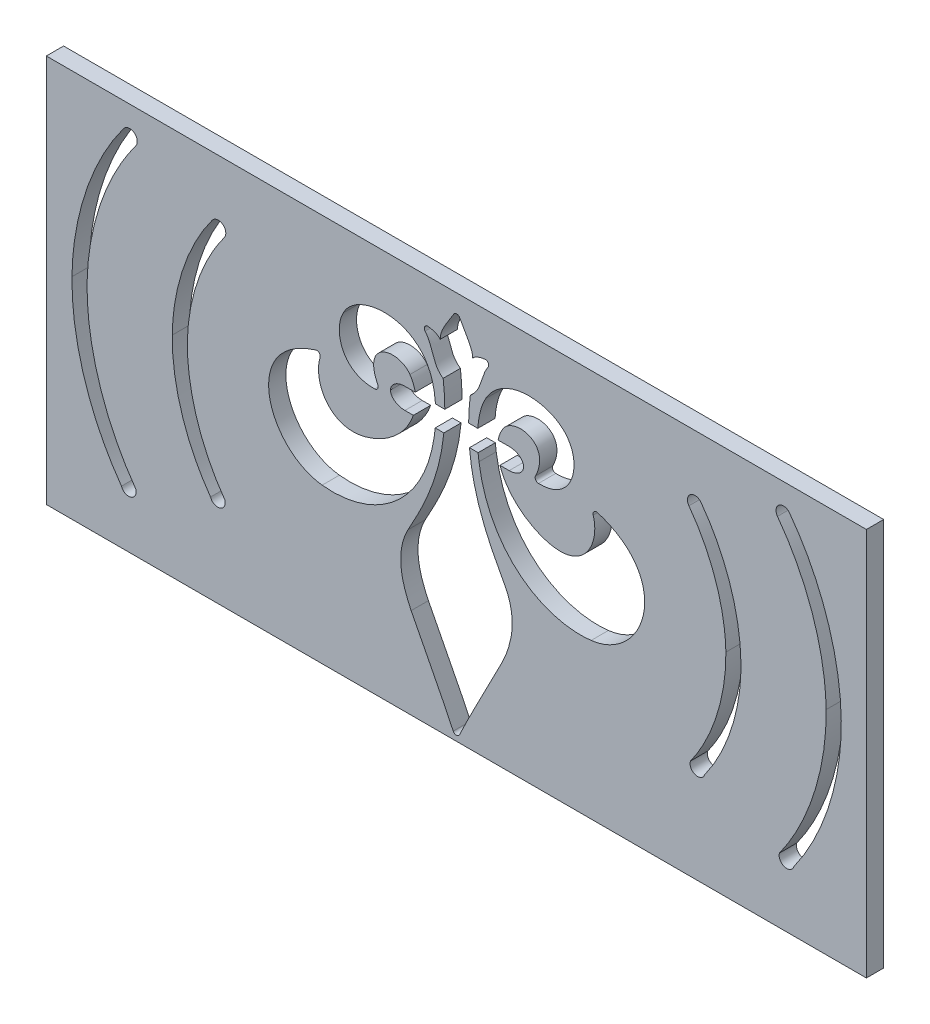
SolidWorks part; units mm, degrees
ref_plane "Front Plane" through (0, 0, 0) normal (0, 0, 1) x (1, 0, 0)
ref_plane "Top Plane" through (0, 0, 0) normal (0, 1, 0) x (1, 0, 0)
ref_plane "Right Plane" through (0, 0, 0) normal (1, 0, 0) x (0, 0, -1)
sketch "Model" plane through (0, 0, 0) normal (0, 0, 1) x (1, 0, 0)
  line L0 (-86.1627, 254.4051) -> (-87.51, 254.4051)
  line L1 (-81.5488, 254.4051) -> (-83.1766, 254.4051)
  line L2 (-82.907, 251.3309) -> (-81.5488, 251.3309)
  line L3 (-87.3892, 251.3309) -> (-86.1192, 251.3309)
  line L4 (-92.4284, 251.3309) -> (-91.1584, 251.3309)
  line L5 (-96.8828, 251.3309) -> (-95.641, 251.3309)
  line L6 (-95.3712, 254.4051) -> (-96.8828, 254.4051)
  line L7 (-91.0142, 254.4051) -> (-92.3852, 254.4051)
  line L9 (-149.6399, 270.1136) -> (-28.9899, 270.1136)
  line L10 (-149.6399, 270.1136) -> (-149.6399, 212.9636)
  line L11 (-149.6399, 212.9636) -> (-28.9899, 212.9636)
  line L12 (-28.9899, 270.1136) -> (-28.9899, 212.9636)
  arc A0 (-125.4824, 226.0089) -> (-123.3695, 226.6771) centre (-124.426, 226.343) ccw
  arc A1 (-123.4553, 260.0716) -> (-125.234, 261.3934) centre (-124.3446, 260.7325) ccw
  arc A2 (-138.5846, 220.8425) -> (-136.4718, 221.5108) centre (-137.5282, 221.1766) ccw
  arc A3 (-136.4853, 265.238) -> (-138.264, 266.5598) centre (-137.3746, 265.8989) ccw
  arc A4 (-101.3097, 251.8565) -> (-100.8693, 252.589) centre (-101.3249, 252.3643) ccw
  arc A5 (-93.4457, 263.7399) -> (-93.9132, 262.9175) centre (-93.5183, 263.2371) ccw
  arc A6 (-88.8174, 267.1636) -> (-89.7055, 267.1819) centre (-89.2665, 266.9262) ccw
  arc A7 (-84.6578, 262.9354) -> (-85.1365, 263.7421) centre (-85.065, 263.2391) ccw
  arc A8 (-77.6787, 252.589) -> (-77.2382, 251.8565) centre (-77.2231, 252.3643) ccw
  arc A9 (-68.5487, 252.4802) -> (-69.1861, 251.8483) centre (-68.6998, 251.9952) ccw
  arc A10 (-89.7766, 214.0218) -> (-88.8534, 214.0212) centre (-89.3149, 214.2336) ccw
  arc A11 (-109.3619, 251.8483) -> (-109.9993, 252.4802) centre (-109.8481, 251.9952) ccw
  arc A12 (-41.7763, 222.4942) -> (-39.6635, 221.826) centre (-40.7199, 222.1601) ccw
  arc A13 (-40.2952, 266.5598) -> (-42.0738, 265.238) centre (-41.1845, 265.8989) ccw
  arc A14 (-53.3252, 261.3934) -> (-55.1038, 260.0716) centre (-54.2145, 260.7325) ccw
  arc A15 (-54.8787, 227.6601) -> (-52.7658, 226.9919) centre (-53.8223, 227.326) ccw
  spline S0 degree 3 poles (-131.1142, 243.816) (-131.1919, 237.591) (-129.1255, 231.0571) (-125.4824, 226.0089) knots 0 0 0 0 1 1 1 1
  spline S1 degree 3 poles (-125.234, 261.3934) (-128.9192, 256.4345) (-131.0371, 249.9938) (-131.1142, 243.816) knots 0 0 0 0 1.00991 1.00991 1.00991 1.00991
  spline S2 degree 3 poles (-128.8933, 244.1428) (-128.7863, 249.7523) (-126.8018, 255.5685) (-123.4553, 260.0716) knots 0 0 0 0 0.989781 0.989781 0.989781 0.989781
  spline S3 degree 3 poles (-123.3695, 226.6771) (-126.9428, 231.6285) (-128.9696, 238.0371) (-128.8933, 244.1428) knots 0 0 0 0 1 1 1 1
  spline S4 degree 3 poles (-145.8693, 243.8758) (-145.9699, 235.8238) (-143.2969, 227.3724) (-138.5846, 220.8425) knots 0 0 0 0 1 1 1 1
  spline S5 degree 3 poles (-138.264, 266.5598) (-143.0208, 260.1588) (-145.7697, 251.8502) (-145.8693, 243.8758) knots 0 0 0 0 1.007595 1.007595 1.007595 1.007595
  spline S6 degree 3 poles (-143.6486, 244.203) (-143.5189, 251.609) (-140.9034, 259.2928) (-136.4853, 265.238) knots 0 0 0 0 0.992225 0.992225 0.992225 0.992225
  spline S7 degree 3 poles (-136.4718, 221.5108) (-141.1143, 227.9439) (-143.7476, 236.2703) (-143.6486, 244.203) knots 0 0 0 0 1 1 1 1
  spline S8 degree 3 poles (-84.9995, 258.7993) (-85.6984, 257.5657) (-86.0494, 256.0206) (-86.1627, 254.4051) knots 0 0 0 0 1 1 1 1
  spline S9 degree 3 poles (-77.2382, 251.8565) (-72.3494, 251.7108) (-71.0944, 256.5725) (-72.6186, 259.2579) knots 0.050131 0.050131 0.050131 0.050131 1 1 1 1
  spline S10 degree 3 poles (-82.4017, 256.2777) (-80.7172, 258.6942) (-75.2407, 257.5318) (-77.6787, 252.589) knots 0 0 0 0 0.958312 0.958312 0.958312 0.958312
  spline S11 degree 3 poles (-83.1766, 254.4051) (-83.053, 255.0746) (-82.7985, 255.7083) (-82.4017, 256.2777) knots 0 0 0 0 1 1 1 1
  spline S12 degree 3 poles (-79.4277, 252.868) (-79.4277, 253.7169) (-80.3774, 254.4051) (-81.5488, 254.4051) knots 0 0 0 0 1 1 1 1
  spline S13 degree 3 poles (-81.5488, 251.3309) (-80.3774, 251.3309) (-79.4277, 252.0189) (-79.4277, 252.868) knots 0 0 0 0 1 1 1 1
  spline S14 degree 3 poles (-69.1861, 251.8483) (-68.0118, 247.9626) (-71.2721, 242.3607) (-78.1228, 245.9626) knots 0.075744 0.075744 0.075744 0.075744 1 1 1 1
  spline S15 degree 3 poles (-69.4879, 235.7237) (-61.5111, 236.6377) (-57.1273, 248.9205) (-68.5487, 252.4802) knots 0 0 0 0 0.972274 0.972274 0.972274 0.972274
  spline S16 degree 3 poles (-85.9922, 250.2414) (-84.5404, 240.0027) (-76.8232, 234.8831) (-69.4879, 235.7237) knots 0 0 0 0 1 1 1 1
  spline S17 degree 3 poles (-86.1192, 251.3309) (-86.0854, 250.9628) (-86.0429, 250.5983) (-85.9922, 250.2414) knots 0 0 0 0 1 1 1 1
  spline S18 degree 3 poles (-82.1688, 236.3628) (-83.8899, 239.5677) (-86.7646, 244.3865) (-87.3892, 251.3309) knots 0 0 0 0 1 1 1 1
  spline S19 degree 3 poles (-82.6302, 226.285) (-81.7486, 228.1162) (-79.9377, 232.2086) (-82.1688, 236.3628) knots 0 0 0 0 1 1 1 1
  spline S20 degree 3 poles (-88.8534, 214.0212) (-87.2569, 217.4908) (-83.5264, 224.424) (-82.6302, 226.285) knots 0.104035 0.104035 0.104035 0.104035 1 1 1 1
  spline S21 degree 3 poles (-95.9666, 226.285) (-95.0705, 224.4242) (-91.3675, 217.4917) (-89.7766, 214.0218) knots 0 0 0 0 0.895912 0.895912 0.895912 0.895912
  spline S22 degree 3 poles (-96.4282, 236.3628) (-98.6593, 232.2086) (-96.8485, 228.1162) (-95.9666, 226.285) knots 0 0 0 0 1 1 1 1
  spline S23 degree 3 poles (-91.1584, 251.3309) (-91.8291, 244.4179) (-94.7187, 239.5458) (-96.4282, 236.3628) knots 0 0 0 0 1 1 1 1
  spline S24 degree 3 poles (-92.5553, 250.2414) (-92.5047, 250.5983) (-92.4618, 250.9626) (-92.4284, 251.3309) knots 0 0 0 0 1 1 1 1
  spline S25 degree 3 poles (-109.0598, 235.7237) (-101.7245, 234.8831) (-94.0073, 240.0025) (-92.5553, 250.2414) knots 0 0 0 0 1 1 1 1
  spline S26 degree 3 poles (-109.9993, 252.4802) (-121.4202, 248.9203) (-117.0365, 236.6376) (-109.0598, 235.7237) knots 0.027728 0.027728 0.027728 0.027728 1 1 1 1
  spline S27 degree 3 poles (-100.4252, 245.9626) (-107.2759, 242.3607) (-110.5361, 247.9625) (-109.3619, 251.8483) knots 0 0 0 0 0.924254 0.924254 0.924254 0.924254
  spline S28 degree 3 poles (-95.641, 251.3309) (-96.3355, 249.2549) (-98.0146, 247.2301) (-100.4252, 245.9626) knots 0 0 0 0 1 1 1 1
  spline S29 degree 3 poles (-99.0038, 252.868) (-99.0038, 252.019) (-98.0542, 251.3309) (-96.8828, 251.3309) knots 0 0 0 0 1 1 1 1
  spline S30 degree 3 poles (-96.8828, 254.4051) (-98.0542, 254.4051) (-99.0038, 253.717) (-99.0038, 252.868) knots 0 0 0 0 1 1 1 1
  spline S31 degree 3 poles (-96.1463, 256.2777) (-95.7494, 255.7083) (-95.4947, 255.0746) (-95.3712, 254.4051) knots 0 0 0 0 1 1 1 1
  spline S32 degree 3 poles (-100.8693, 252.589) (-103.3072, 257.5318) (-97.8308, 258.6942) (-96.1463, 256.2777) knots 0.041687 0.041687 0.041687 0.041687 1 1 1 1
  spline S33 degree 3 poles (-105.9293, 259.2579) (-107.4534, 256.5723) (-106.1984, 251.7108) (-101.3097, 251.8565) knots 0 0 0 0 0.949869 0.949869 0.949869 0.949869
  spline S34 degree 3 poles (-93.5485, 258.7993) (-96.4633, 263.9429) (-104.1659, 262.8624) (-105.9293, 259.2579) knots 0 0 0 0 1 1 1 1
  spline S35 degree 3 poles (-92.3852, 254.4051) (-92.4986, 256.0206) (-92.8495, 257.5657) (-93.5485, 258.7993) knots 0 0 0 0 1 1 1 1
  spline S36 degree 3 poles (-91.2591, 258.237) (-91.0959, 256.9032) (-91.0221, 255.6264) (-91.0142, 254.4051) knots 0 0 0 0 1 1 1 1
  spline S37 degree 3 poles (-93.9132, 262.9175) (-92.6262, 261.3271) (-92.8782, 259.2799) (-91.2591, 258.237) knots 0.168492 0.168492 0.168492 0.168492 1 1 1 1
  spline S38 degree 3 poles (-91.6925, 262.9822) (-91.9607, 263.3576) (-92.5992, 263.6175) (-93.4457, 263.7399) knots 0 0 0 0 0.657659 0.657659 0.657659 0.657659
  spline S39 degree 3 poles (-89.7055, 267.1819) (-90.62, 265.6113) (-91.6925, 264.3909) (-91.6925, 262.9822) knots 0.148939 0.148939 0.148939 0.148939 1 1 1 1
  spline S40 degree 3 poles (-86.9049, 262.9822) (-86.9049, 264.1313) (-87.9526, 265.5272) (-88.8174, 267.1636) knots 0 0 0 0 0.851528 0.851528 0.851528 0.851528
  spline S41 degree 3 poles (-85.1365, 263.7421) (-85.9906, 263.6207) (-86.6352, 263.3599) (-86.9049, 262.9822) knots 0.338377 0.338377 0.338377 0.338377 1 1 1 1
  spline S42 degree 3 poles (-87.2653, 258.072) (-85.4647, 259.55) (-85.7211, 261.5095) (-84.6578, 262.9354) knots 0 0 0 0 0.814236 0.814236 0.814236 0.814236
  spline S43 degree 3 poles (-87.51, 254.4051) (-87.4975, 255.5745) (-87.4217, 256.7951) (-87.2653, 258.072) knots 0 0 0 0 1 1 1 1
  spline S44 degree 3 poles (-72.6186, 259.2579) (-74.3821, 262.8624) (-82.0847, 263.9427) (-84.9995, 258.7993) knots 0 0 0 0 1 1 1 1
  spline S45 degree 3 poles (-78.1228, 245.9626) (-80.5334, 247.2301) (-82.2123, 249.2549) (-82.907, 251.3309) knots 0 0 0 0 1 1 1 1
  spline S46 degree 3 poles (-34.9105, 244.203) (-34.8158, 236.6141) (-37.335, 228.6485) (-41.7763, 222.4942) knots 0 0 0 0 1 1 1 1
  spline S47 degree 3 poles (-42.0738, 265.238) (-37.6557, 259.2928) (-35.0402, 251.609) (-34.9105, 244.203) knots 0 0 0 0 0.992225 0.992225 0.992225 0.992225
  spline S48 degree 3 poles (-39.6635, 221.826) (-35.1524, 228.077) (-32.5936, 236.1676) (-32.6898, 243.8758) knots 0 0 0 0 1 1 1 1
  spline S49 degree 3 poles (-32.6898, 243.8758) (-32.7894, 251.8502) (-35.5383, 260.1588) (-40.2952, 266.5598) knots 0 0 0 0 1.007595 1.007595 1.007595 1.007595
  spline S50 degree 3 poles (-55.1038, 260.0716) (-51.7573, 255.5684) (-49.7728, 249.7523) (-49.6658, 244.1428) knots 0 0 0 0 0.989781 0.989781 0.989781 0.989781
  spline S51 degree 3 poles (-52.7658, 226.9919) (-49.3239, 231.7614) (-47.3715, 237.9346) (-47.4449, 243.816) knots 0 0 0 0 1 1 1 1
  spline S52 degree 3 poles (-49.6658, 244.1428) (-49.5938, 238.3808) (-51.5066, 232.3329) (-54.8787, 227.6601) knots 0 0 0 0 1 1 1 1
  spline S53 degree 3 poles (-47.4449, 243.816) (-47.522, 249.9938) (-49.64, 256.4345) (-53.3252, 261.3934) knots 0 0 0 0 1.00991 1.00991 1.00991 1.00991
  point P98 (-89.3149, 212.9636)
  dimension "D1" = 113.1795
  dimension "D2" = 52.6927
  dimension "D3" = 57.15
  dimension "D4" = 120.65
  dimension "D5" = 1.27
  dimension "D6" = 0
extrude "Boss-Extrude1" add sketch "Model" along normal blind 2.54
